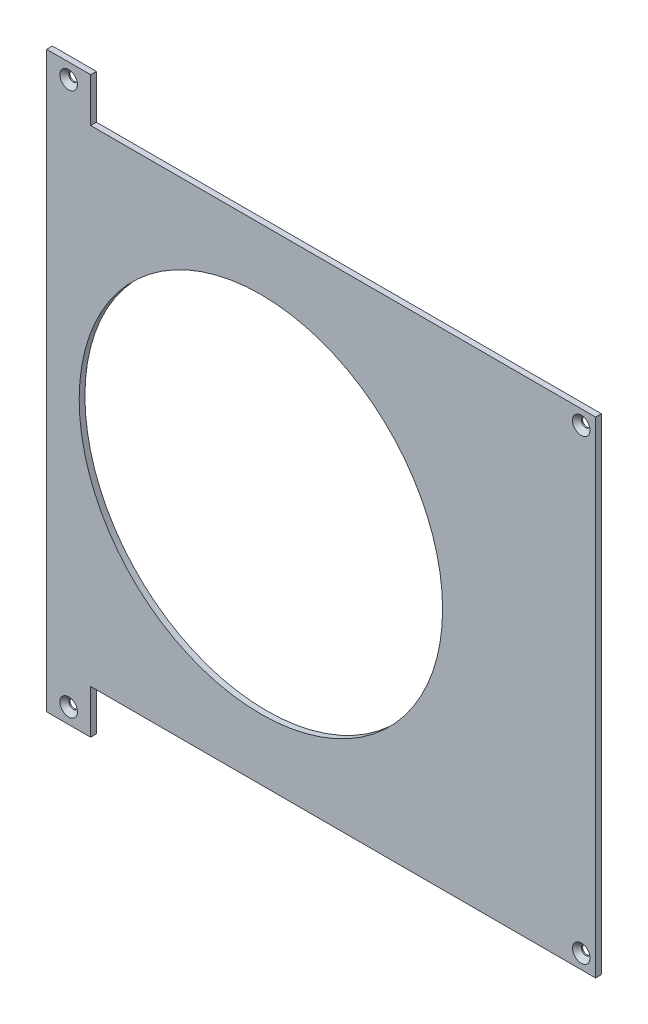
SolidWorks part; units mm, degrees
ref_plane "Ebene vorne" through (0, 0, 0) normal (0, 0, 1) x (1, 0, 0)
ref_plane "Ebene oben" through (0, 0, 0) normal (0, 1, 0) x (1, 0, 0)
ref_plane "Ebene rechts" through (0, 0, 0) normal (1, 0, 0) x (0, 0, -1)
sketch "Skizze1" plane through (0, 0, 0) normal (0, 0, 1) x (1, 0, 0)
  line L0 (15.0007, 0) -> (15.0007, -300)
  line L1 (15.0007, -300) -> (38.0007, -300)
  line L2 (469.0007, -300) -> (15.0007, -300) construction
  line L3 (38.0007, -300) -> (38.0007, -277)
  line L4 (469.0007, -277) -> (15.0007, -277) construction
  line L6 (302.0007, -277) -> (302.0007, -23)
  line L8 (15.0007, -23) -> (469.0007, -23) construction
  line L9 (38.0007, -23) -> (38.0007, 0)
  line L10 (15.0007, 0) -> (469.0007, 0) construction
  line L11 (38.0007, 0) -> (15.0007, 0)
  line L12 (38.0007, -23) -> (302.0007, -23)
  line L19 (302.0007, -277) -> (38.0007, -277)
  dimension "D1" = 23
  dimension "D2" = 23
  dimension "D3" = 264
extrude "Aufsatz-Linear austragen1" add sketch "Skizze1" along normal blind 3 contours L11 L0 L1 L3 L19 L6 L12 L9
hole_wizard "Formsenkung für M4 Senkschraube mit Innensechskant1" positions "Skizze2" profile "Skizze3" countersink size "M4" standard "DIN" end condition through all
sketch "Skizze2" plane through (0, 0, 3) normal (0, 0, 1) x (1, 0, 0)
  line L1 (15.0007, 0) -> (15.0007, -300) construction
  line L2 (38.0007, 0) -> (15.0007, 0) construction
  line L3 (15.0007, -300) -> (38.0007, -300) construction
  line L4 (302.0007, -277) -> (302.0007, -23) construction
  line L5 (38.0007, -23) -> (302.0007, -23) construction
  line L6 (302.0007, -277) -> (38.0007, -277) construction
  point P0 (26.5007, -8)
  point P2 (26.5007, -292)
  point P13 (294.5007, -30.5)
  point P15 (294.5007, -269.5)
  dimension "D1" = 11.5
  dimension "D2" = 11.5
  dimension "D3" = 8
  dimension "D4" = 8
  dimension "D5" = 7.5
  dimension "D6" = 7.5
  dimension "D7" = 7.5
  dimension "D8" = 7.5
sketch "Skizze3" plane through (26.5007, -8, 3) normal (1, 0, 0) x (0, -1, 0)
  line L0 (0, 0) -> (0, 3)
  line L1 (0, 3) -> (2.25, 3)
  line L2 (2.25, 3) -> (2.25, 2.34)
  line L3 (2.25, 2.34) -> (4.59, 0)
  line L5 (4.59, 0) -> (0, 0)
  line L6 (-2.25, 2.34) -> (-4.59, 0) construction
  line L11 (0, -6.35) -> (0, 107.95) construction
  dimension "Bohrerdurchmesser" = 4.5
  dimension "Bohrungstiefe" = 3
  dimension "Senkdurchmesser (Oben)" = 9.18
  dimension "Senkwinkel (Oben)" = 90
sketch "Skizze4" plane through (0, 0, 3) normal (0, 0, 1) x (1, 0, 0)
  line L0 (15.0007, 0) -> (15.0007, -300) construction
  circle A0 centre (127.0007, -150) radius 95
  dimension "D1" = 190
  dimension "D2" = 112
extrude "Schnitt-Linear austragen1" cut sketch "Skizze4" against normal blind 10
